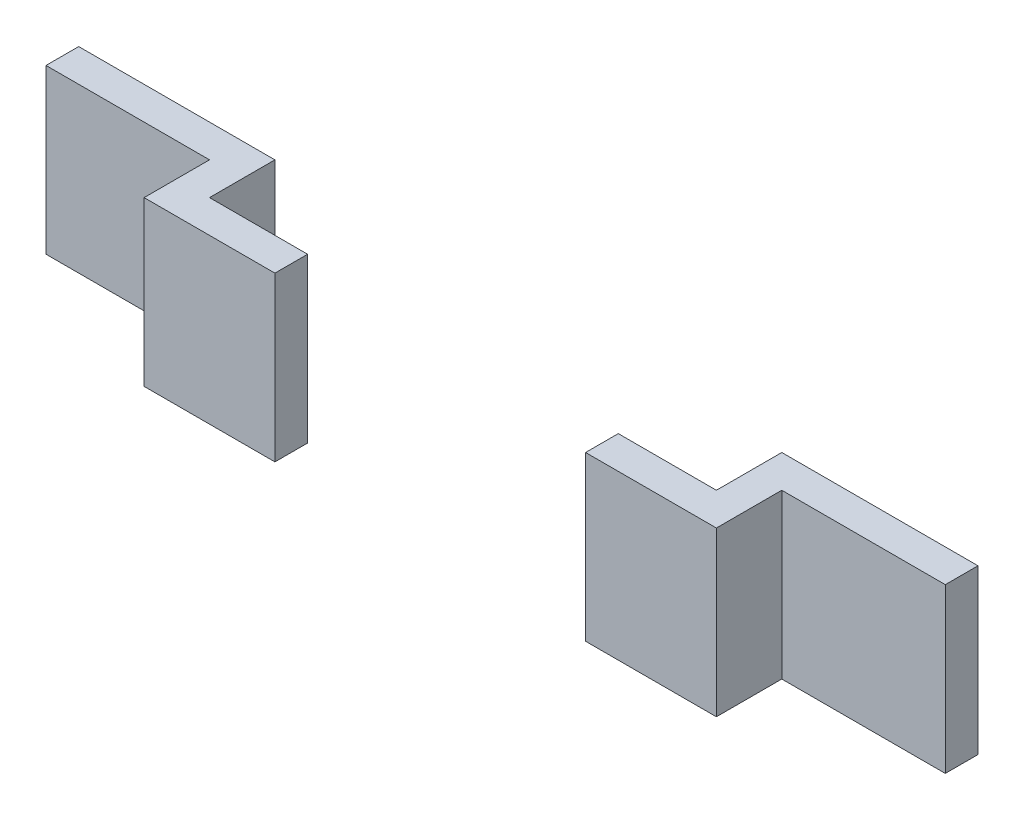
SolidWorks part; units mm, degrees
ref_plane "Front Plane" through (0, 0, 0) normal (0, 0, 1) x (1, 0, 0)
ref_plane "Top Plane" through (0, 0, 0) normal (0, 1, 0) x (1, 0, 0)
ref_plane "Right Plane" through (0, 0, 0) normal (1, 0, 0) x (0, 0, -1)
sketch "Sketch1" plane through (0, 0, 0) normal (0, 0, 1) x (1, 0, 0)
  line L1 (-8.75, 2.5) -> (8.75, 2.5)
  line L2 (-8.75, 2.5) -> (-8.75, -2.5)
  line L3 (-8.75, -2.5) -> (8.75, -2.5)
  line L4 (8.75, 2.5) -> (8.75, -2.5)
  line L5 (-8.75, 2.5) -> (8.75, -2.5) construction
  line L6 (-8.75, -2.5) -> (8.75, 2.5) construction
  line L7 (-13.75, 2.5) -> (13.75, 2.5)
  line L8 (-13.75, 2.5) -> (-13.75, -2.5)
  line L9 (-13.75, -2.5) -> (13.75, -2.5)
  line L10 (13.75, 2.5) -> (13.75, -2.5)
  line L11 (-13.75, 2.5) -> (13.75, -2.5) construction
  line L12 (-13.75, -2.5) -> (13.75, 2.5) construction
  point P0 (0, 0)
  point P6 (0, 0)
  dimension "D1" = 17.5
  dimension "D2" = 5
  dimension "D3" = 5
extrude "Boss-Extrude1" add sketch "Sketch1" along normal blind 1 contours L8 L9 L2 L7 | L10 L7 L4 L9
sketch "Sketch2" plane through (0, 0, 0) normal (0, 0, 1) x (1, 0, 0)
  line L0 (-8.75, 2.5) -> (-8.75, -2.5) construction
  line L1 (-8.75, 2.5) -> (-7.75, 2.5)
  line L2 (-8.75, 2.5) -> (-8.75, -2.5)
  line L3 (-8.75, -2.5) -> (-7.75, -2.5)
  line L4 (-7.75, 2.5) -> (-7.75, -2.5)
  line L5 (8.75, 2.5) -> (7.75, 2.5)
  line L6 (8.75, 2.5) -> (8.75, -2.5)
  line L7 (8.75, -2.5) -> (7.75, -2.5)
  line L8 (7.75, 2.5) -> (7.75, -2.5)
  line L9 (8.75, 2.5) -> (8.75, -2.5) construction
  point P10 (-8.75, -2.0623)
  point P13 (0, 0)
  point P14 (-8.75, -2.7308)
  point P16 (8.75, -2.7308)
  point P19 (8.75, -2.5)
  dimension "D1" = 1
extrude "Boss-Extrude2" add sketch "Sketch2" along normal blind 3 contours L4 L3 L2 L1 | L8 L7 L6 L5
sketch "Sketch3" plane through (0, 0, 3) normal (0, 0, 1) x (1, 0, 0)
  line L0 (8.75, -2.5) -> (7.75, -2.5) construction
  line L1 (-8.75, 2.5) -> (-4.75, 2.5)
  line L2 (-8.75, 2.5) -> (-8.75, -2.5)
  line L3 (-8.75, -2.5) -> (-4.75, -2.5)
  line L4 (-4.75, 2.5) -> (-4.75, -2.5)
  line L5 (8.75, 2.5) -> (4.75, 2.5)
  line L6 (8.75, 2.5) -> (8.75, -2.5)
  line L7 (8.75, -2.5) -> (4.75, -2.5)
  line L8 (4.75, 2.5) -> (4.75, -2.5)
  point P10 (-8.75, -2.5)
  point P12 (8.75, -2.7308)
  line M9 (-7.75, -2.5) -> (-7.75, 2.5)
  dimension "D1" = 4
extrude "Boss-Extrude3" add sketch "Sketch3" against normal blind 1 contours L4 L1 L3 M9 | L5 L8 L7 L6
